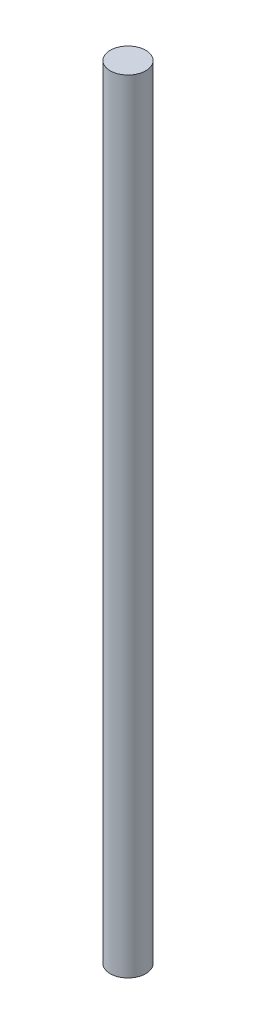
SolidWorks part; units mm, degrees
ref_plane "Front Plane" through (0, 0, 0) normal (0, 0, 1) x (1, 0, 0)
ref_plane "Top Plane" through (0, 0, 0) normal (0, 1, 0) x (1, 0, 0)
ref_plane "Right Plane" through (0, 0, 0) normal (1, 0, 0) x (0, 0, -1)
sketch "Sketch1" plane through (0, 0, 0) normal (0, 1, 0) x (1, 0, 0)
  circle A0 centre (0, 0) radius 2.5
  dimension "D1" = 5
extrude "Boss-Extrude1" add sketch "Sketch1" along normal blind 110
